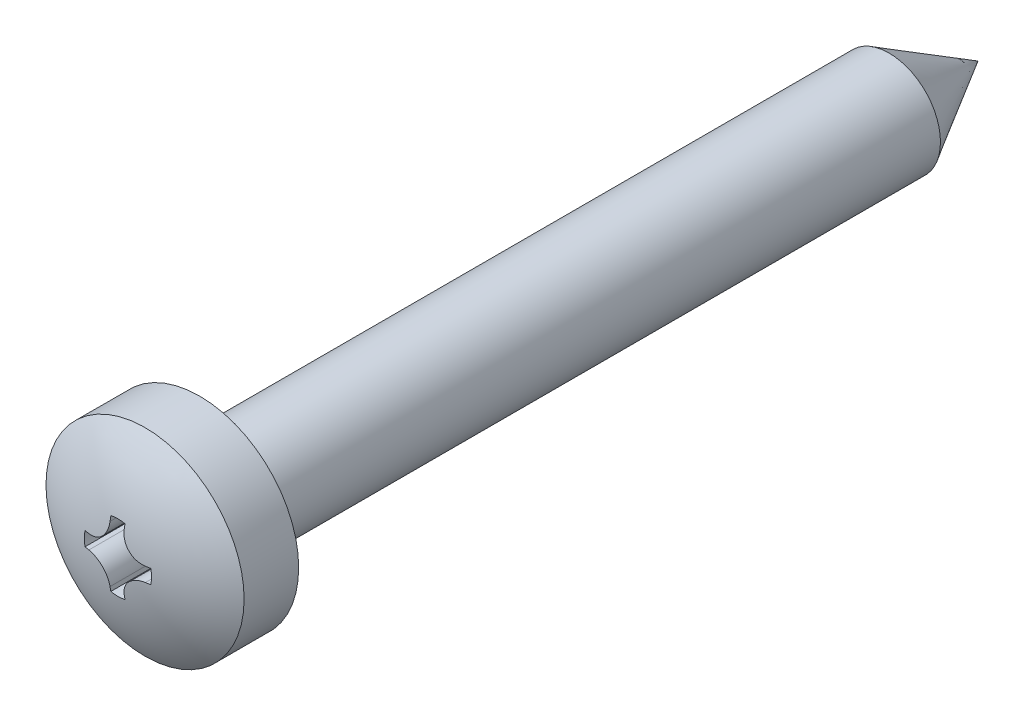
SolidWorks part; units mm, degrees
revolve "基体-旋转" add sketch "草图8" angle 360 about L0
sketch "草图8" plane through (0, 0, 0) normal (1, 0, 0) x (0, 0, -1)
  line L0 (-11.71, 0) -> (1.33, 0) construction
  line L1 (0, 0) -> (-24.4, 0)
  line L4 (-23.5425, 2.8) -> (-22, 2.8)
  line L5 (-22, 2.8) -> (-22, 1.45)
  line L6 (-22, 1.45) -> (-2.5115, 1.45)
  line L7 (-2.5115, 1.45) -> (0, 0)
  arc A0 (-24.4, 0) -> (-23.5425, 2.8) centre (-19.4, 0) cw
  dimension "D4" = 5
  dimension "D1" = 22
  dimension "D2" = 30
  dimension "D5" = 2.9
  dimension "D3" = 5.6
  dimension "D6" = 2.4
cosmetic thread "装饰螺纹线1" parameters "D1"=18.3, "D2"=2.5114
extrude "切除-拉伸2" cut sketch "草图7" against normal blind 1.2
sketch "草图7" plane through (0, 0, 24.4) normal (0, 0, 1) x (1, 0, 0)
  line L0 (-7.1, 0) -> (5.9, 0) construction
  line L1 (0, 7.5) -> (0, -7) construction
  line L2 (0.2, 0.9287) -> (0.2, 0.7975)
  line L3 (0, 0) -> (4.9858, 4.9858) construction
  line L4 (0.9287, 0.2) -> (0.7975, 0.2)
  line L5 (0.9287, -0.2) -> (0.7975, -0.2)
  line L6 (0.2, -0.9287) -> (0.2, -0.7975)
  line L7 (-0.2, -0.9287) -> (-0.2, -0.7975)
  line L8 (-0.9287, -0.2) -> (-0.7975, -0.2)
  line L9 (-0.9287, 0.2) -> (-0.7975, 0.2)
  line L10 (-0.2, 0.9287) -> (-0.2, 0.7975)
  line L11 (0, 0) -> (-4.9858, 4.9858) construction
  arc A0 (-0.2, 0.9287) -> (0.2, 0.9287) centre (0, 0) cw
  arc A1 (0.9287, -0.2) -> (0.9287, 0.2) centre (0, 0) ccw
  arc A2 (0.7975, 0.2) -> (0.2, 0.7975) centre (0.7975, 0.7975) cw
  arc A3 (-0.7975, 0.2) -> (-0.2, 0.7975) centre (-0.7975, 0.7975) ccw
  arc A4 (-0.2, -0.9287) -> (0.2, -0.9287) centre (0, 0) ccw
  arc A5 (0.7975, -0.2) -> (0.2, -0.7975) centre (0.7975, -0.7975) ccw
  arc A6 (-0.9287, -0.2) -> (-0.9287, 0.2) centre (0, 0) cw
  arc A7 (-0.7975, -0.2) -> (-0.2, -0.7975) centre (-0.7975, -0.7975) cw
  dimension "D10" = 0.95
  dimension "D1" = 0.5975
  dimension "D2" = 0.5975
material "冷镦钢"
ref_plane "前视" through (0, 0, 0) normal (0, 0, 1) x (1, 0, 0)
ref_plane "上视" through (0, 0, 0) normal (0, 1, 0) x (1, 0, 0)
ref_plane "右视" through (0, 0, 0) normal (1, 0, 0) x (0, 0, -1)
sketch "尺寸草图" plane through (0, 0, 0) normal (1, 0, 0) x (0, 0, -1)
  line L0 (-22, 5.6) -> (-22, 0)
  line L1 (-22, 0) -> (0, 0)
  line L2 (0, 0) -> (0, 2.9)
  point P4 (-19.6, 0)
  point P6 (0, 1.1)
  point P7 (-20.9, 0)
  point P8 (-22, 5.5)
  point P9 (-22, 0.6)
  point P10 (-1.9, 0)
  point P11 (-1.2, 0)
  point P12 (-21.52, 0)
  point P13 (-18.5, 0)
  point P14 (-19.4, 0)
  dimension "l" = 22
  dimension "E" = 5.6
  dimension "K" = 2.4
  dimension "d" = 2.9
  dimension "P" = 1.1
  dimension "A" = 1.1
  dimension "R" = 0.1
  dimension "Rf" = 5
  dimension "HM" = 1.9
  dimension "HH" = 1.2
  dimension "HE" = 0.48
  dimension "Da" = 3.5
  dimension "Yc" = 2.6
ref_plane "基准面6" through (0, 0, 24.4) normal (0, 0, 1) x (1, 0, 0)
sketch "草图9" plane through (0, 0, 0) normal (1, 0, 0) x (0, 0, -1)
  line L0 (-20.9, 1.45) -> (-19.8, 1.45)
  line L1 (-20.9, 1.45) -> (-20.4875, 0.9)
  line L2 (-20.2125, 0.9) -> (-20.4875, 0.9)
  line L3 (-20.2125, 0.9) -> (-19.8, 1.45)
  line L4 (-11.71, 0) -> (1.33, 0) construction
  line L5 (-22, -2.8) -> (-22, 2.8) construction
  line L6 (-6.912, 0) -> (-2.6011, 0) construction
  line L7 (-23.2, 0) -> (-24.3089, 0) construction
  dimension "D1" = 1.1
  dimension "D2" = 0.275
  dimension "D3" = 0.55
  dimension "D4" = 1.45
  dimension "D5" = 1.1
revolve "切除-旋转1" [suppressed] cut sketch "草图9" angle 360 about L6
pattern_linear "阵列(线性)1" [suppressed] count 15 spacing 1.375
fillet "圆角1" radius 0.1 1 edges at (1.45, 0, 22)
equation "\"D16@基准面6\" = \"l@尺寸草图\"+\"K@尺寸草图\""
equation "\"D1@草图8\" = \"l@尺寸草图\""
equation "\"D6@草图8\" = \"K@尺寸草图\""
equation "\"D5@草图8\" = \"d@尺寸草图\""
equation "\"D3@草图8\" = \"E@尺寸草图\""
equation "\"D4@草图8\" = \"Rf@尺寸草图\""
equation "\"D10@草图7\" = \"HM@尺寸草图\"/2"
equation "\"D1@切除-拉伸2\" = \"HH@尺寸草图\""
equation "\"D1@草图9\" = \"P@尺寸草图\""
equation "\"D2@草图9\" = \"D1@草图9\"/4"
equation "\"D3@草图9\" = \"D1@草图9\"/2"
equation "\"D4@草图9\" = \"d@尺寸草图\"/2"
equation "\"D5@草图9\" = \"A@尺寸草图\""
equation "\"D3@阵列(线性)1\" = \"A@尺寸草图\"*5/4"
equation "\"D1@阵列(线性)1\" = (\"l@尺寸草图\"-\"A@尺寸草图\")/\"D3@阵列(线性)1\""
equation "\"D2@装饰螺纹线1\" = \"d@尺寸草图\"*0.866"
equation "\"D1@装饰螺纹线1\" = \"l@尺寸草图\"-\"Yc@尺寸草图\"-\"A@尺寸草图\""
equation "\"D1@圆角1\" = \"R@尺寸草图\""
